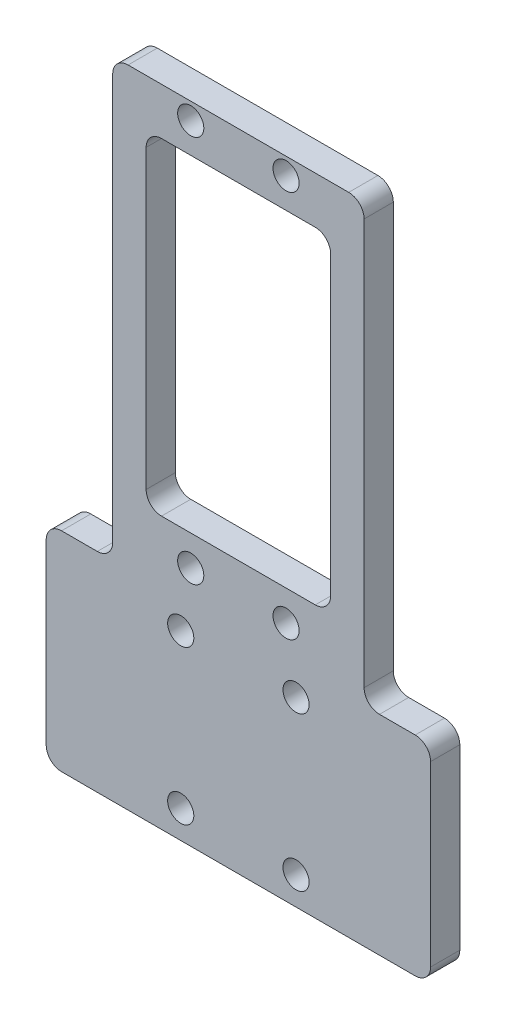
SolidWorks part; units mm, degrees
ref_plane "Front Plane" through (0, 0, 0) normal (0, 0, 1) x (1, 0, 0)
ref_plane "Top Plane" through (0, 0, 0) normal (0, 1, 0) x (1, 0, 0)
ref_plane "Right Plane" through (0, 0, 0) normal (1, 0, 0) x (0, 0, -1)
sketch "Sketch1" plane through (0, 0, 0) normal (0, 0, 1) x (1, 0, 0)
  line L0 (22.8792, 70.3) -> (11.8208, 70.3) construction
  line L1 (3, 70.3) -> (31.7, 70.3)
  line L2 (31.7, -13.6411) -> (40.35, -13.6411)
  line L3 (41.6076, 13.5) -> (45.5932, 13.5) construction
  line L4 (27.35, 42.9) -> (19.1646, 42.9) construction
  line L5 (42.35, -11.6411) -> (42.35, 11.5)
  line L6 (23.55, 68.1) -> (11.15, 68.1) construction
  line L7 (7.35, 64.1908) -> (27.35, 64.1908)
  line L8 (1, 68.3) -> (1, 15.5)
  line L9 (3, -13.6411) -> (31.7, -13.6411)
  line L10 (33.7, 15.5) -> (33.7, 68.3)
  line L12 (5.35, 62.1908) -> (5.35, 23.654)
  line L13 (7.35, 21.654) -> (27.35, 21.654)
  line L14 (29.35, 62.1908) -> (29.35, 23.654)
  line L15 (40.35, 13.5) -> (35.7, 13.5)
  line L16 (3, -13.6411) -> (-5.65, -13.6411)
  line L17 (-7.65, -11.6411) -> (-7.65, 11.5)
  line L18 (-5.65, 13.5) -> (-1, 13.5)
  line L19 (17.35, -13.6411) -> (17.35, -19.9861) construction
  arc A0 (27.35, 21.654) -> (29.35, 23.654) centre (27.35, 23.654) ccw
  arc A1 (5.35, 23.654) -> (7.35, 21.654) centre (7.35, 23.654) ccw
  circle A2 centre (11.15, 17.7) radius 1.7
  circle A4 centre (9.85, 10) radius 1.7
  circle A5 centre (24.85, 10) radius 1.7
  circle A6 centre (9.85, -10) radius 1.7
  circle A7 centre (24.85, -10) radius 1.7
  circle A8 centre (23.55, 17.7) radius 1.7
  arc A10 (1, 68.3) -> (3, 70.3) centre (3, 68.3) cw
  arc A11 (33.7, 68.3) -> (31.7, 70.3) centre (31.7, 68.3) ccw
  circle A12 centre (23.55, 68.1) radius 1.7
  circle A13 centre (11.15, 68.1) radius 1.7
  arc A14 (27.35, 64.1908) -> (29.35, 62.1908) centre (27.35, 62.1908) cw
  arc A15 (7.35, 64.1908) -> (5.35, 62.1908) centre (7.35, 62.1908) ccw
  arc A16 (-7.65, 11.5) -> (-5.65, 13.5) centre (-5.65, 11.5) cw
  arc A17 (-1, 13.5) -> (1, 15.5) centre (-1, 15.5) ccw
  arc A18 (35.7, 13.5) -> (33.7, 15.5) centre (35.7, 15.5) cw
  arc A19 (42.35, 11.5) -> (40.35, 13.5) centre (40.35, 11.5) ccw
  arc A20 (40.35, -13.6411) -> (42.35, -11.6411) centre (40.35, -11.6411) ccw
  arc A21 (-5.65, -13.6411) -> (-7.65, -11.6411) centre (-5.65, -11.6411) cw
  point P11 (-7.65, 13.5)
  point P37 (17.35, 68.1)
  point P38 (17.35, 64.1908)
  point P57 (1, 13.5)
  point P60 (33.7, 13.5)
  point P63 (42.35, 13.5)
  dimension "D6" = 3.4
  dimension "D7" = 3.4
  dimension "D8" = 3.4
  dimension "D9" = 3.4
  dimension "D2" = 3.4
  dimension "D10" = 3.4
  dimension "D11" = 2
  dimension "D13" = 2
  dimension "D3" = 20
  dimension "D4" = 20
  dimension "D5" = 15
  dimension "D12" = 12
  dimension "D14" = 25
  dimension "D15" = 25
extrude "Boss-Extrude1" add sketch "Sketch1" along normal blind 3.8
